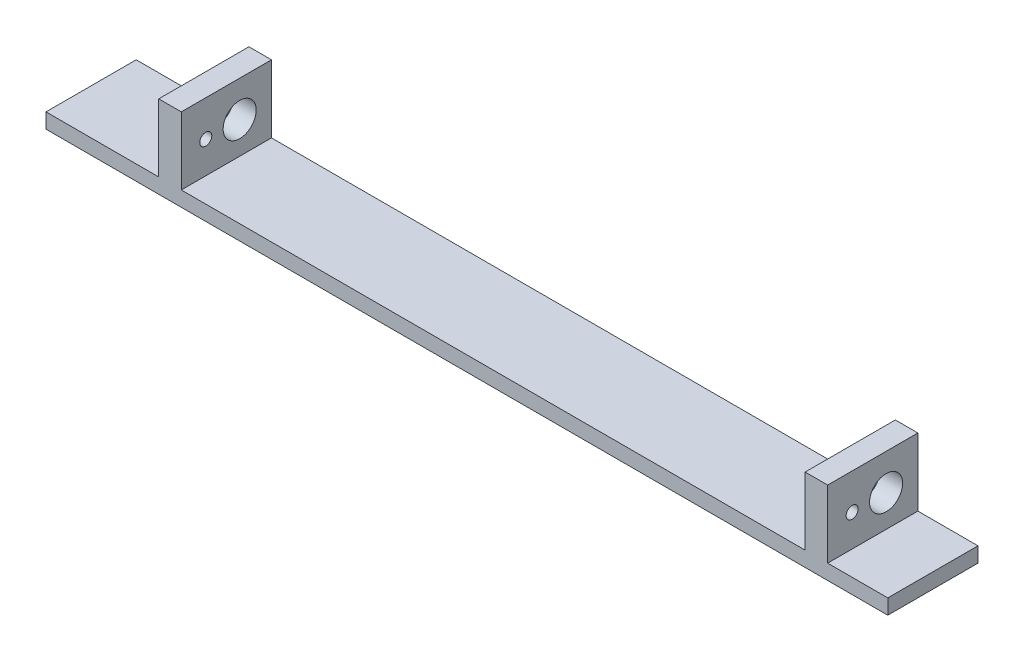
SolidWorks part; units mm, degrees
ref_plane "Front Plane" through (0, 0, 0) normal (0, 0, 1) x (1, 0, 0)
ref_plane "Top Plane" through (0, 0, 0) normal (0, 1, 0) x (1, 0, 0)
ref_plane "Right Plane" through (0, 0, 0) normal (1, 0, 0) x (0, 0, -1)
sketch "Sketch2" plane through (0, 0, 0) normal (1, 0, 0) x (0, 0, -1)
  line L1 (-30, 5) -> (30, 5)
  line L2 (-30, 5) -> (-30, -5)
  line L3 (-30, -5) -> (30, -5)
  line L4 (30, 5) -> (30, -5)
  line L5 (-30, 5) -> (30, -5) construction
  line L6 (-30, -5) -> (30, 5) construction
  point P0 (0, 0)
  dimension "D1" = 10
  dimension "D2" = 60
extrude "Boss-Extrude1" add sketch "Sketch2" along normal blind 560
sketch "Sketch4" plane through (0, 5, 0) normal (0, 1, 0) x (1, 0, 0)
  line L1 (560, 30) -> (0, 30) construction
  line L2 (75, 30) -> (90, 30)
  line L3 (90, 30) -> (90, -30)
  line L4 (560, -30) -> (0, -30) construction
  line L5 (90, -30) -> (75, -30)
  line L6 (75, -30) -> (75, 30)
  dimension "D2" = 15
extrude "Boss-Extrude2" add sketch "Sketch4" along normal blind 45
sketch "Sketch5" plane through (0, 5, 0) normal (0, 1, 0) x (1, 0, 0)
  line L1 (560, 30) -> (90, 30) construction
  line L2 (520, 30) -> (520, -30)
  line L3 (560, -30) -> (90, -30) construction
  line L5 (505, -30) -> (505, 30)
  line L6 (505, 30) -> (520, 30)
  line L7 (520, -30) -> (505, -30)
  dimension "D2" = 15
extrude "Boss-Extrude3" add sketch "Sketch5" along normal blind 45
sketch "Sketch6" plane through (75, 0, 0) normal (-1, 0, 0) x (0, 0, 1)
  line L0 (-30, 5) -> (-30, 26.15)
  line L1 (-30, 50) -> (-30, 5) construction
  circle A0 centre (-8.85, 26.15) radius 11
  circle A1 centre (13.718, 26.15) radius 4
  dimension "D3" = 22
  dimension "D5" = 8
  dimension "D1" = 21.15
  dimension "D2" = 21.15
extrude "Cut-Extrude1" cut sketch "Sketch6" against normal blind 455 contours A0 | A1
